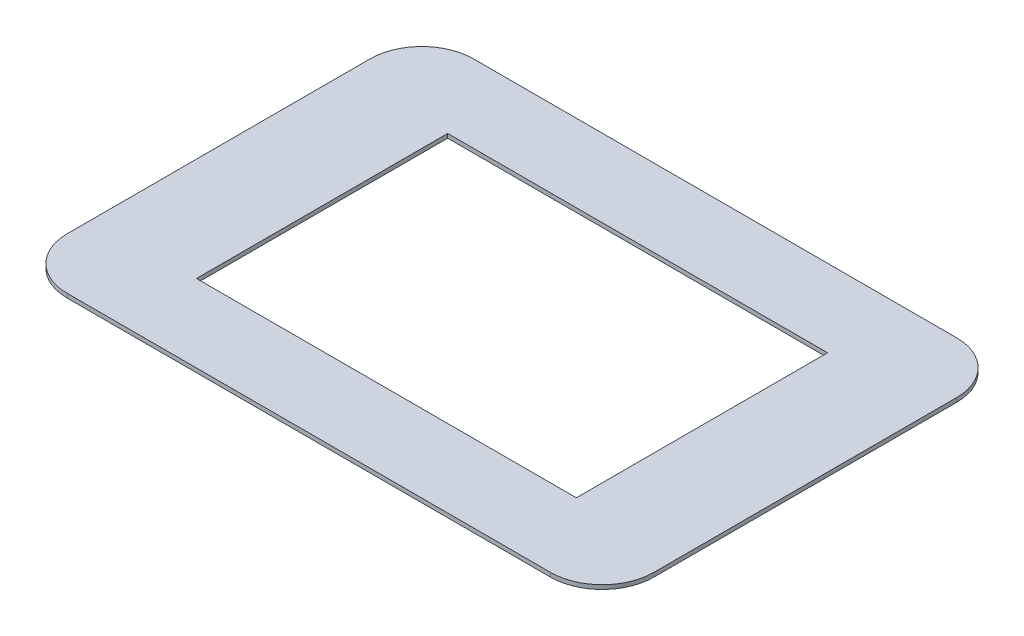
SolidWorks part; units mm, degrees
material "1060 Сплав"
ref_plane "Front" through (0, 0, 0) normal (0, 0, 1) x (1, 0, 0)
ref_plane "Top" through (0, 0, 0) normal (0, 1, 0) x (1, 0, 0)
ref_plane "Right" through (0, 0, 0) normal (1, 0, 0) x (0, 0, -1)
sketch "Эскиз1" plane through (0, 0, 0) normal (0, 1, 0) x (1, 0, 0)
  line L1 (10, 0) -> (103.5, 0)
  line L2 (0, 10) -> (0, 68.6)
  line L3 (10, 78.6) -> (103.5, 78.6)
  line L4 (113.5, 10) -> (113.5, 68.6)
  line L5 (20, 15) -> (93.5, 15)
  line L6 (20, 15) -> (20, 63.6)
  line L7 (20, 63.6) -> (93.5, 63.6)
  line L8 (93.5, 15) -> (93.5, 63.6)
  arc A0 (103.5, 78.6) -> (113.5, 68.6) centre (103.5, 68.6) cw
  arc A1 (10, 0) -> (0, 10) centre (10, 10) cw
  arc A2 (0, 68.6) -> (10, 78.6) centre (10, 68.6) cw
  arc A3 (103.5, 0) -> (113.5, 10) centre (103.5, 10) ccw
  point P11 (113.5, 78.6)
  point P14 (0, 0)
  point P17 (0, 78.6)
  dimension "D7" = 10
  dimension "D8" = 10
  dimension "D1" = 48.6
  dimension "D2" = 73.5
  dimension "D3" = 113.5
  dimension "D4" = 78.6
  dimension "D5" = 15
  dimension "D6" = 20
extrude "Бобышка-Вытянуть1" add sketch "Эскиз1" along normal blind 0.8
